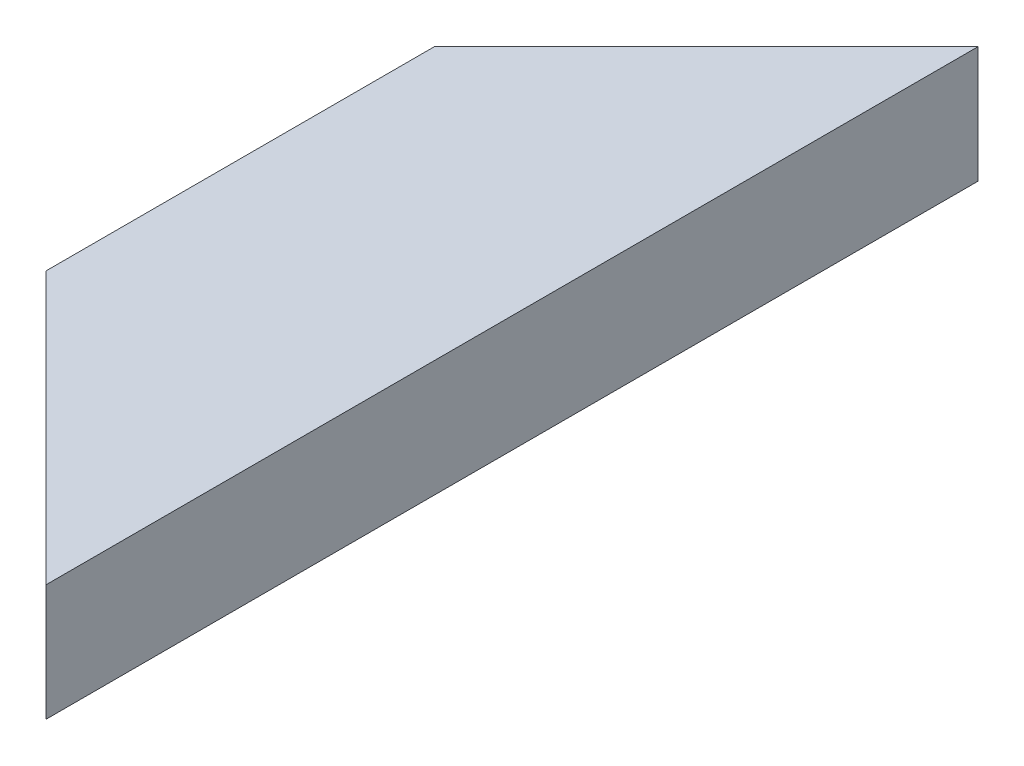
SolidWorks part; units mm, degrees
material "Pine"
ref_plane "Front Plane" through (0, 0, 0) normal (0, 0, 1) x (1, 0, 0)
ref_plane "Top Plane" through (0, 0, 0) normal (0, 1, 0) x (1, 0, 0)
ref_plane "Right Plane" through (0, 0, 0) normal (1, 0, 0) x (0, 0, -1)
sketch "Sketch1" plane through (0, 0, 0) normal (0, 0, 1) x (1, 0, 0)
  line L1 (44.45, -19.05) -> (-44.45, -19.05)
  line L2 (44.45, -19.05) -> (44.45, 19.05)
  line L3 (44.45, 19.05) -> (-44.45, 19.05)
  line L4 (-44.45, -19.05) -> (-44.45, 19.05)
  line L5 (44.45, -19.05) -> (-44.45, 19.05) construction
  line L6 (44.45, 19.05) -> (-44.45, -19.05) construction
  point P0 (0, 0)
  dimension "D1" = 88.9
  dimension "D2" = 38.1
extrude "Boss-Extrude1" add sketch "Sketch1" along normal blind 304.8
sketch "Sketch2" plane through (0, 19.05, 0) normal (0, 1, 0) x (1, 0, 0)
  line L0 (44.45, 0) -> (-44.45, 0)
  line L1 (-44.45, 0) -> (-44.45, -88.9)
  line L2 (-44.45, -304.8) -> (-44.45, 0) construction
  line L3 (-44.45, -88.9) -> (44.45, 0)
  line L4 (-44.45, -304.8) -> (44.45, -304.8)
  line L5 (-44.45, -304.8) -> (-44.45, -215.9)
  line L6 (-44.45, -215.9) -> (44.45, -304.8)
  line M7 (44.45, 0) -> (-44.45, 0)
  line M8 (-44.45, 0) -> (-44.45, -304.8)
  line M9 (-44.45, -304.8) -> (44.45, -304.8)
extrude "Cut-Extrude1" cut sketch "Sketch2" against normal through all contours L6 L3 M8 M9 | L6 L3 M8 M7 | L6 L1 L3
